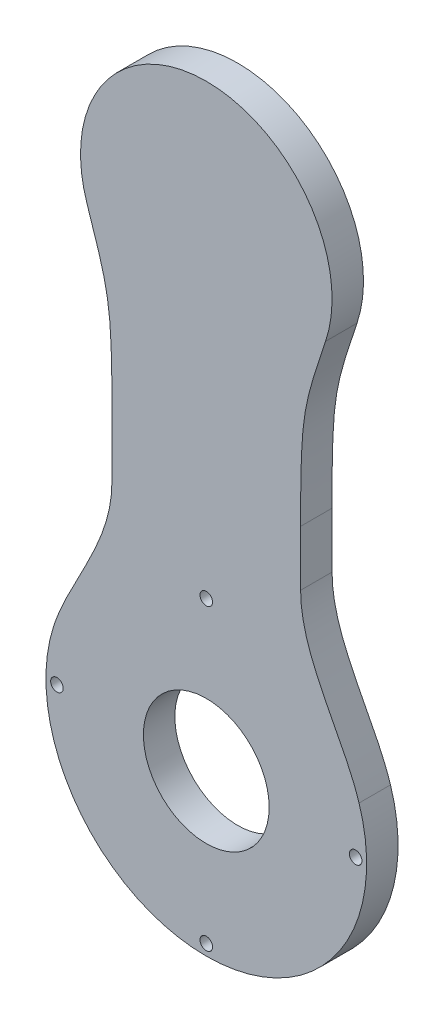
SolidWorks part; units mm, degrees
ref_plane "Front Plane" through (0, 0, 0) normal (0, 0, 1) x (1, 0, 0)
ref_plane "Top Plane" through (0, 0, 0) normal (0, 1, 0) x (1, 0, 0)
ref_plane "Right Plane" through (0, 0, 0) normal (1, 0, 0) x (0, 0, -1)
sketch "Sketch2" plane through (0, 0, 0) normal (0, 0, 1) x (1, 0, 0)
  line L2 (-51, 0) -> (51, 0) construction
  line L3 (-30, 41.2432) -> (-30, 123.5425)
  line L4 (30, 41.2432) -> (30, 123.5425)
  line L5 (-30, 123.5425) -> (30, 123.5425) construction
  line L6 (0, 0) -> (0, 150) construction
  arc A0 (-51, 0) -> (51, 0) centre (0, 0) ccw
  arc A2 (-51, 0) -> (-30, 41.2432) centre (0, 0) cw
  arc A3 (30, 41.2432) -> (51, 0) centre (0, 0) cw
  arc A4 (30, 123.5425) -> (-30, 123.5425) centre (0, 150) ccw
  spline S0 degree 3 poles (37.9326, 137.3069) (30.7364, 115.8012) (30, 113.5983) (30, 82.3928) knots 0 0 0 0 1 1 1 1
  spline S1 degree 3 poles (30, 64.7866) (30, 46.7344) (43.4581, 31.6008) (48.5936, 15.4811) knots 0 0 0 0 1 1 1 1
  spline S2 degree 3 poles (-37.9326, 137.3069) (-30.7364, 115.8012) (-30, 113.5983) (-30, 82.3928) knots 0 0 0 0 1 1 1 1
  spline S3 degree 3 poles (-30, 64.7866) (-30, 46.7344) (-43.4581, 31.6008) (-48.5936, 15.4811) knots 0 0 0 0 1 1 1 1
  dimension "D1" = 102
  dimension "D3" = 60
  dimension "D2" = 80
  dimension "D5" = 150
  dimension "D4" = 30
extrude "Boss-Extrude1" add sketch "Sketch2" along normal blind 10 contours S1 L4 A3 | L3 S3 A2 | A4 S2 L3 | S0 A4 L4 | L4 A4 L3 A2 A0 A3
sketch "Sketch3" plane through (0, 0, 10) normal (0, 0, 1) x (1, 0, 0)
  circle A0 centre (0, 0) radius 47.5 construction
  circle A1 centre (0, -47.5) radius 2
  circle A2 centre (-47.5, 0) radius 2
  circle A3 centre (0, 47.5) radius 2
  circle A4 centre (47.5, 0) radius 2
  circle A7 centre (0, 0) radius 20
  point P14 (0, 0)
  dimension "D1" = 95
  dimension "D2" = 4
  dimension "D3" = 4
  dimension "D4" = 40
extrude "Cut-Extrude1" cut sketch "Sketch3" against normal up to surface (10 mm away)
equation "\"ArmWidth\"= 60"
equation "\"arm\"=30"
